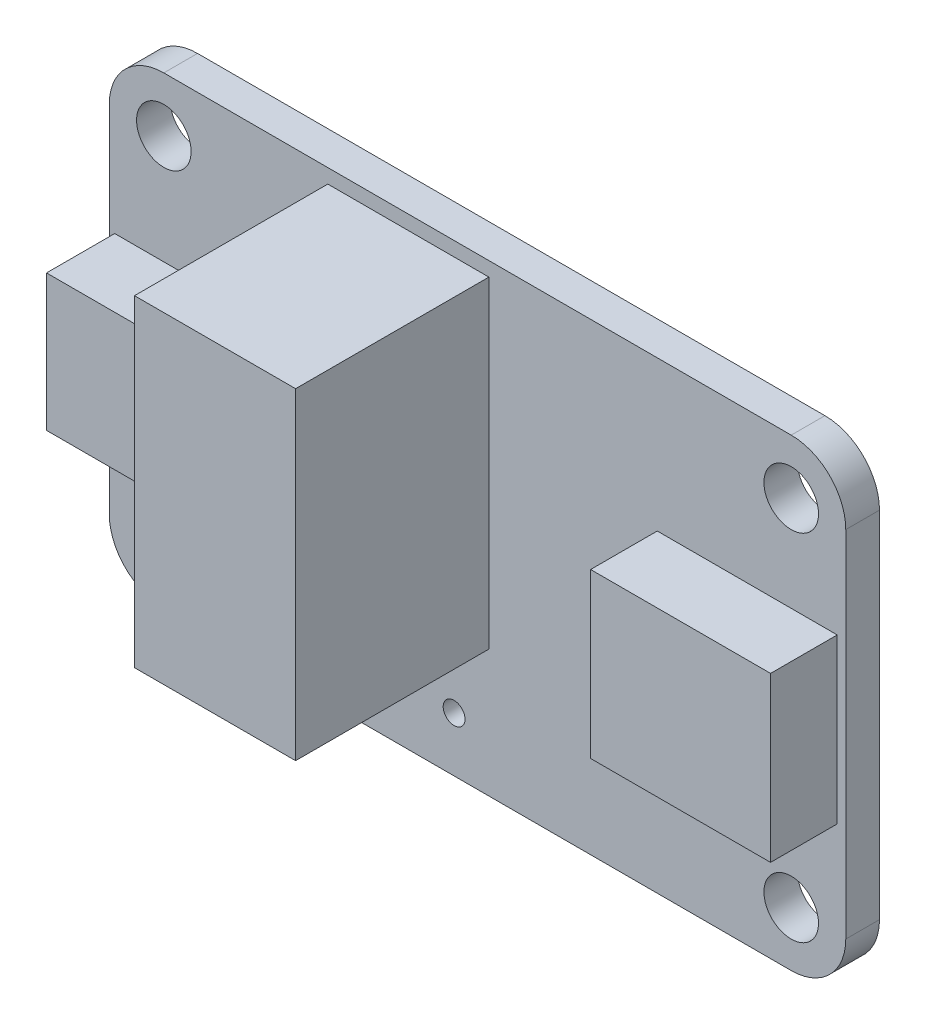
SolidWorks part; units mm, degrees
ref_plane "Front Plane" through (0, 0, 0) normal (0, 0, 1) x (1, 0, 0)
ref_plane "Top Plane" through (0, 0, 0) normal (0, 1, 0) x (1, 0, 0)
ref_plane "Right Plane" through (0, 0, 0) normal (1, 0, 0) x (0, 0, -1)
sketch "Sketch1" plane through (0, 0, 0) normal (0, 0, 1) x (1, 0, 0)
  line L1 (-17.145, -10.795) -> (17.145, -10.795)
  line L2 (-17.145, -10.795) -> (-17.145, 10.795)
  line L3 (-17.145, 10.795) -> (17.145, 10.795)
  line L4 (17.145, -10.795) -> (17.145, 10.795)
  line L5 (-17.145, -10.795) -> (17.145, 10.795) construction
  line L6 (-17.145, 10.795) -> (17.145, -10.795) construction
  circle A0 centre (-14.605, 8.255) radius 1.27
  circle A1 centre (-14.605, -8.255) radius 1.27
  circle A2 centre (14.605, -8.255) radius 1.27
  circle A3 centre (14.605, 8.255) radius 1.27
  circle A4 centre (-6.1698, -8.255) radius 0.508
  circle A5 centre (-3.6298, -8.255) radius 0.508
  circle A6 centre (-1.0898, -8.255) radius 0.508
  point P0 (0, 0)
  point P20 (0, 0)
  dimension "D5" = 2.54
  dimension "D6" = 14.605
  dimension "D8" = 1.016
  dimension "D1" = 34.29
  dimension "D2" = 21.59
  dimension "D3" = 16.51
  dimension "D4" = 29.21
  dimension "D7" = 8.255
  dimension "D9" = 2.54
  dimension "D10" = 2.54
extrude "Boss-Extrude1" add sketch "Sketch1" along normal blind 1.57
fillet "Fillet1" radius 2.54 4 edges at (17.145, 10.795, 0.785) (17.145, -10.795, 0.785) (-17.145, -10.795, 0.785) (-17.145, 10.795, 0.785)
sketch "Sketch2" plane through (0, 0, 1.57) normal (0, 0, 1) x (1, 0, 0)
  line L1 (-6.9697, 10.1298) -> (0.5303, 10.1298)
  line L2 (-6.9697, 10.1298) -> (-6.9697, -4.8702)
  line L3 (-6.9697, -4.8702) -> (0.5303, -4.8702)
  line L4 (0.5303, 10.1298) -> (0.5303, -4.8702)
  line L5 (-6.9697, 10.1298) -> (0.5303, -4.8702) construction
  line L6 (-6.9697, -4.8702) -> (0.5303, 10.1298) construction
  point P0 (-3.2197, 2.6298)
  point P5 (-3.8721, 4.1843)
  point P6 (-0.5995, -2.2858)
  dimension "D1" = 15
  dimension "D2" = 7.5
extrude "Boss-Extrude2" add sketch "Sketch2" along normal blind 9
sketch "Sketch3" plane through (0, 0, 1.57) normal (0, 0, 1) x (1, 0, 0)
  line L0 (-17.145, 8.255) -> (-17.145, -8.255) construction
  line L1 (-16.891, 3.175) -> (-12.192, 3.175)
  line L2 (-16.891, 3.175) -> (-16.891, -3.175)
  line L3 (-16.891, -3.175) -> (-12.192, -3.175)
  line L4 (-12.192, 3.175) -> (-12.192, -3.175)
  line L5 (-16.891, 3.175) -> (-12.192, -3.175) construction
  line L6 (-16.891, -3.175) -> (-12.192, 3.175) construction
  point P0 (-14.5415, 0)
  point P5 (0, 0)
  dimension "D1" = 6.35
  dimension "D2" = 4.699
  dimension "D3" = 0.254
extrude "Boss-Extrude3" add sketch "Sketch3" along normal blind 3.175
sketch "Sketch4" plane through (-16.891, 0, 0) normal (-1, 0, 0) x (0, 0, 1)
  line L0 (4.745, 3.175) -> (4.745, -3.175) construction
  line L1 (1.824, 2.921) -> (4.491, 2.921)
  line L2 (1.824, 2.921) -> (1.824, -2.921)
  line L3 (1.824, -2.921) -> (4.491, -2.921)
  line L4 (4.491, 2.921) -> (4.491, -2.921)
  line L5 (1.824, 2.921) -> (4.491, -2.921) construction
  line L6 (1.824, -2.921) -> (4.491, 2.921) construction
  line L7 (4.745, 3.175) -> (1.57, 3.175) construction
  line L8 (4.745, -3.175) -> (1.57, -3.175) construction
  line L9 (1.57, 8.255) -> (1.57, -8.255) construction
  point P0 (3.1575, 0)
  dimension "D1" = 0.254
  dimension "D2" = 0.254
  dimension "D3" = 0.254
  dimension "D4" = 0.254
extrude "Cut-Extrude1" cut sketch "Sketch4" against normal blind 3.175
sketch "Sketch6" plane through (0, 0, 0) normal (0, 1, 0) x (1, 0, 0)
  line L1 (16.7474, -4.673) -> (8.3686, -4.673)
  line L2 (8.3686, -4.673) -> (8.3686, -1.57)
  line L3 (14.605, -1.57) -> (-14.605, -1.57) construction
  line L4 (8.3686, -1.57) -> (16.7474, -1.57)
  line L5 (16.7474, -1.57) -> (16.7474, -4.673)
extrude "Boss-Extrude4" add sketch "Sketch6" along normal mid plane 7.62
